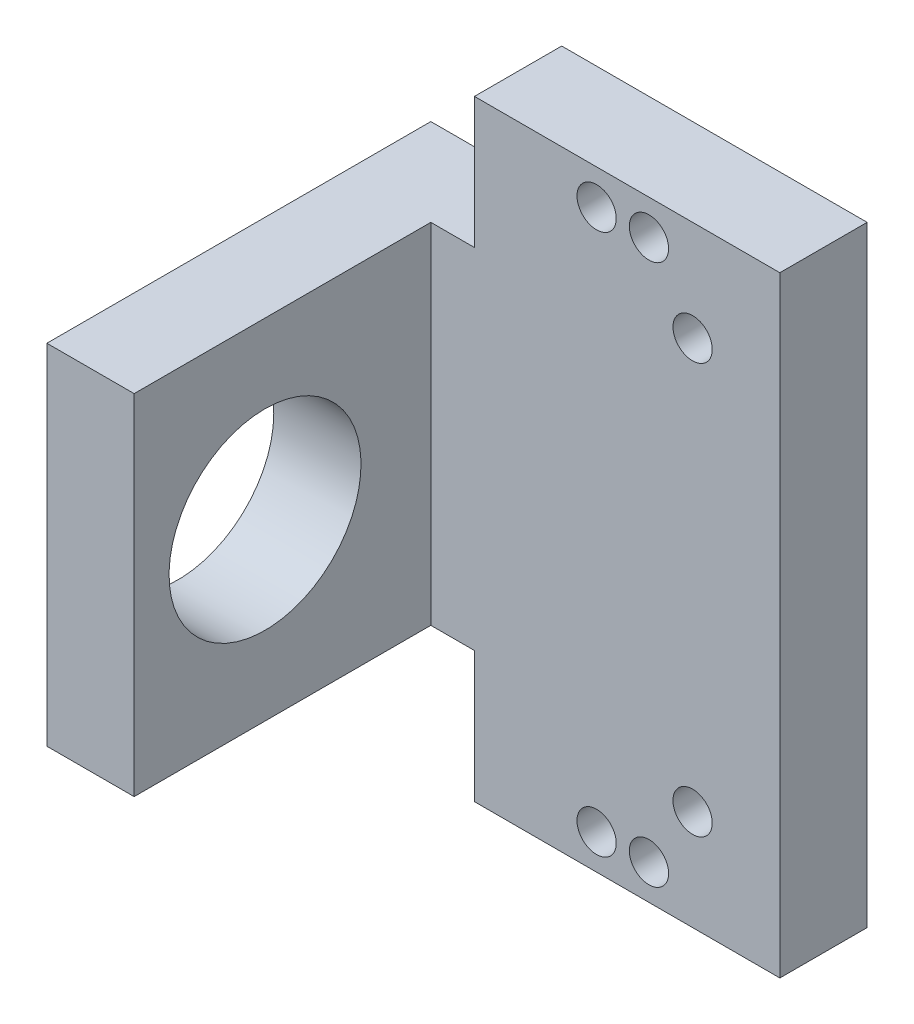
SolidWorks part; units mm, degrees
material "SKD11淬火HRC56-60"
ref_plane "前基準面" through (0, 0, 0) normal (0, 0, 1) x (1, 0, 0)
ref_plane "上基準面" through (0, 0, 0) normal (0, 1, 0) x (1, 0, 0)
ref_plane "右基準面" through (0, 0, 0) normal (1, 0, 0) x (0, 0, -1)
sketch "草图1" plane through (0, 0, 0) normal (0, 0, 1) x (1, 0, 0)
  line L1 (0, 0) -> (50, 0)
  line L2 (0, 0) -> (0, 70)
  line L3 (0, 70) -> (50, 70)
  line L4 (50, 0) -> (50, 70)
  dimension "D1" = 50
  dimension "D2" = 70
extrude "凸台-拉伸1" add sketch "草图1" along normal blind 10
sketch "草图2" plane through (0, 0, 10) normal (0, 0, 1) x (1, 0, 0)
  line L0 (0, 0) -> (50, 0) construction
  line L1 (0, 70) -> (10, 70)
  line L2 (0, 70) -> (0, 0)
  line L3 (0, 0) -> (10, 0)
  line L4 (10, 70) -> (10, 0)
  dimension "D1" = 10
extrude "凸台-拉伸2" add sketch "草图2" along normal blind 34
sketch "草图3" plane through (10, 0, 0) normal (1, 0, 0) x (0, 0, -1)
  line L0 (-10, 35) -> (-38.916, 35) construction
  line L3 (-10, 0) -> (-10, 70) construction
  circle A0 centre (-29, 35) radius 11
  dimension "D1" = 22
  dimension "D2" = 19
extrude "切除-拉伸1" cut sketch "草图3" against normal blind 32
sketch "草图4" plane through (0, 0, 10) normal (0, 0, 1) x (1, 0, 0)
  line L0 (50, 35) -> (28.8099, 35) construction
  line L1 (50, 0) -> (50, 70) construction
  circle A0 centre (40, 11.5) radius 2.25
  circle A1 centre (40, 58.5) radius 2.25
  dimension "D1" = 4.5
  dimension "D2" = 47
  dimension "D3" = 10
extrude "切除-拉伸2" cut sketch "草图4" against normal through all
sketch "草图5" plane through (0, 0, 10) normal (0, 0, 1) x (1, 0, 0)
  line L0 (50, 35) -> (22.2785, 35) construction
  line L1 (50, 0) -> (50, 70) construction
  circle A0 centre (35, 66) radius 2.25
  circle A1 centre (35, 4) radius 2.25
  circle A2 centre (29, 4) radius 2.25
  circle A3 centre (29, 66) radius 2.25
  dimension "D1" = 62
  dimension "D2" = 4.5
  dimension "D3" = 15
  dimension "D4" = 6
extrude "切除-拉伸3" cut sketch "草图5" against normal through all
sketch "草图6" plane through (10, 0, 0) normal (1, 0, 0) x (0, 0, -1)
  line L0 (-10, 0) -> (-10, 70) construction
  line L1 (-44, 0) -> (-10, 0)
  line L2 (-44, 0) -> (-44, 15)
  line L3 (-44, 15) -> (-10, 15)
  line L4 (-10, 0) -> (-10, 15)
  line L5 (-44, 35) -> (-10, 35) construction
  line L6 (-44, 0) -> (-44, 70) construction
  line L7 (-10, 70) -> (-10, 55)
  line L8 (-44, 55) -> (-10, 55)
  line L9 (-44, 70) -> (-44, 55)
  line L10 (-44, 70) -> (-10, 70)
  dimension "D1" = 40
extrude "切除-拉伸4" cut sketch "草图6" against normal through all
sketch "草图7" plane through (0, 0, 10) normal (0, 0, 1) x (1, 0, 0)
  line L0 (0, 0) -> (50, 0) construction
  line L1 (0, 15) -> (15, 15)
  line L2 (0, 15) -> (0, 0)
  line L3 (0, 0) -> (15, 0)
  line L4 (15, 15) -> (15, 0)
  line L5 (50, 35) -> (37.2423, 35) construction
  line L6 (50, 0) -> (50, 70) construction
  line L7 (15, 55) -> (15, 70)
  line L8 (0, 70) -> (15, 70)
  line L9 (0, 55) -> (0, 70)
  line L10 (0, 55) -> (15, 55)
  dimension "D1" = 15
extrude "切除-拉伸5" cut sketch "草图7" against normal through all
